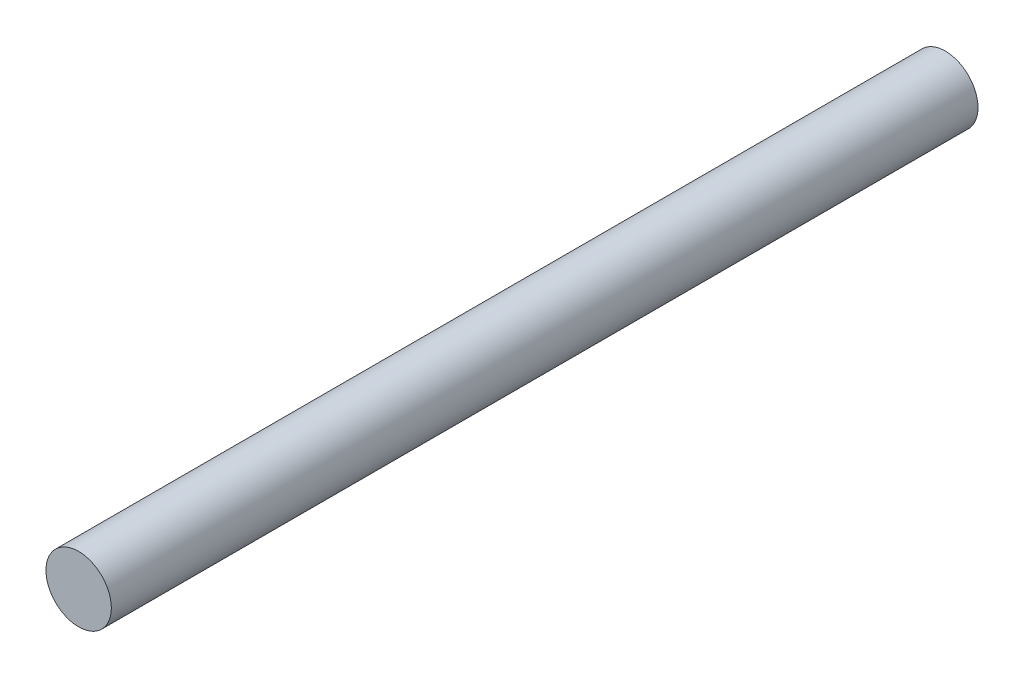
SolidWorks part; units mm, degrees
ref_plane "Front Plane" through (0, 0, 0) normal (0, 0, 1) x (1, 0, 0)
ref_plane "Top Plane" through (0, 0, 0) normal (0, 1, 0) x (1, 0, 0)
ref_plane "Right Plane" through (0, 0, 0) normal (1, 0, 0) x (0, 0, -1)
sketch "Sketch1" plane through (0, 0, 0) normal (0, 0, 1) x (1, 0, 0)
  circle A0 centre (0, 0) radius 4
  dimension "D1" = 8
extrude "Boss-Extrude1" add sketch "Sketch1" along normal blind 106
